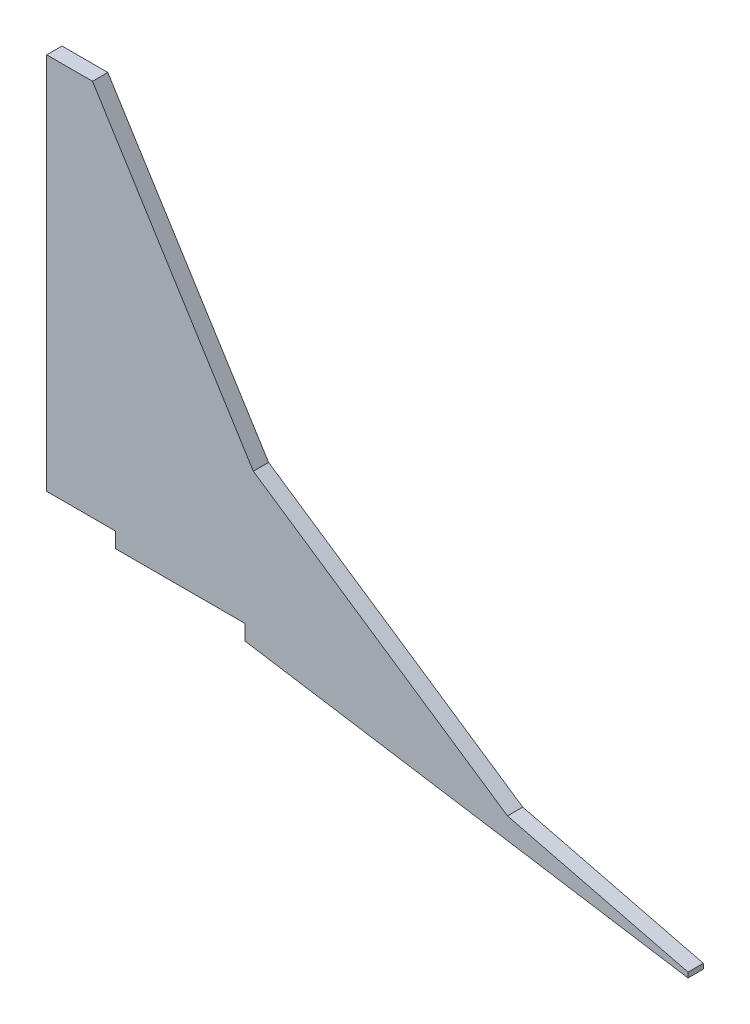
SolidWorks part; units mm, degrees
ref_plane "Front Plane" through (0, 0, 0) normal (0, 0, 1) x (1, 0, 0)
ref_plane "Top Plane" through (0, 0, 0) normal (0, 1, 0) x (1, 0, 0)
ref_plane "Right Plane" through (0, 0, 0) normal (1, 0, 0) x (0, 0, -1)
sketch "Five-point nose support web profile" plane through (0, 0, 0) normal (0, 0, 1) x (1, 0, 0)
  line L0 (94.5, 8) -> (103, 8)
  line L1 (103, 8) -> (103, 7)
  line L2 (103, 7) -> (132, 2.4)
  line L3 (132, 2.4) -> (132, 2.7334)
  line L4 (132, 2.7334) -> (120.174, 5.682)
  line L5 (120.174, 5.682) -> (103.5292, 16.909)
  line L6 (103.5292, 16.909) -> (93, 33.7592)
  line L7 (93, 33.7592) -> (90, 33.7592)
  line L8 (90, 33.7592) -> (90, 9)
  line L9 (90, 9) -> (94.5, 9)
  line L10 (94.5, 9) -> (94.5, 8)
extrude "Five-point nose support web" add sketch "Five-point nose support web profile" along normal blind 1
